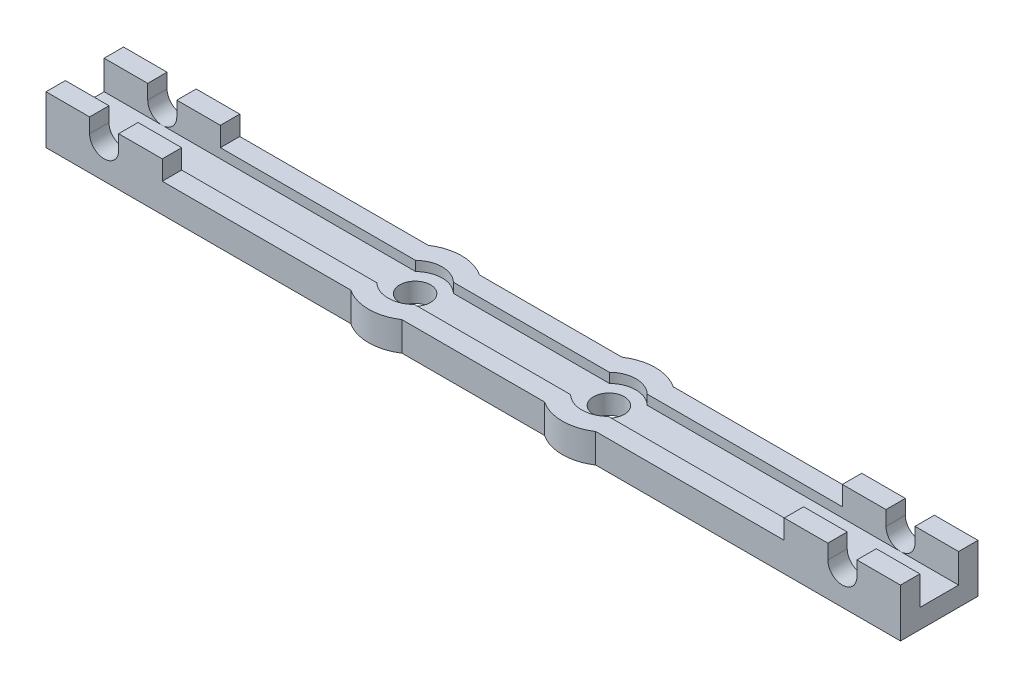
SolidWorks part; units mm, degrees
ref_plane "Front Plane" through (0, 0, 0) normal (0, 0, 1) x (1, 0, 0)
ref_plane "Top Plane" through (0, 0, 0) normal (0, 1, 0) x (1, 0, 0)
ref_plane "Right Plane" through (0, 0, 0) normal (1, 0, 0) x (0, 0, -1)
sketch "Sketch1" plane through (0, 0, 0) normal (0, 1, 0) x (1, 0, 0)
  line L1 (0, -4) -> (44.1, -4)
  line L2 (0, -4) -> (0, 4)
  line L3 (0, 4) -> (44.1, 4)
  line L4 (44.1, -4) -> (44.1, 4)
  point P4 (0, 0)
  dimension "D1" = 44.1
  dimension "D2" = 8
extrude "Boss-Extrude1" add sketch "Sketch1" along normal blind 2
sketch "Sketch2" plane through (0, 2, 0) normal (0, 1, 0) x (1, 0, 0)
  line L1 (44.1, 4) -> (32.1, 4)
  line L2 (44.1, 4) -> (44.1, 2)
  line L3 (44.1, 2) -> (32.1, 2)
  line L4 (32.1, 4) -> (32.1, 2)
  line L5 (44.1, -4) -> (32.1, -4)
  line L6 (44.1, -4) -> (44.1, -2)
  line L7 (44.1, -2) -> (32.1, -2)
  line L8 (32.1, -4) -> (32.1, -2)
  dimension "D1" = 2
  dimension "D2" = 12
extrude "Boss-Extrude2" add sketch "Sketch2" along normal blind 3
sketch "Sketch3" plane through (0, 0, 4) normal (0, 0, 1) x (1, 0, 0)
  line L0 (44.1, 5) -> (44.1, 0) construction
  line L1 (32.1, 5) -> (44.1, 5) construction
  line L2 (36.6, 3.5) -> (36.6, 5)
  line L3 (36.6, 5) -> (39.6, 5)
  line L4 (39.6, 5) -> (39.6, 3.5)
  arc A0 (36.6, 3.5) -> (39.6, 3.5) centre (38.1, 3.5) ccw
  dimension "D1" = 3
  dimension "D2" = 6
  dimension "D3" = 1.5
extrude "Cut-Extrude1" cut sketch "Sketch3" against normal through all
sketch "Sketch4" plane through (0, 2, 0) normal (0, 1, 0) x (1, 0, 0)
  line L0 (0, 4) -> (0, -4) construction
  line L1 (32.1, -4) -> (0, -4)
  line L2 (32.1, -4) -> (32.1, -2)
  line L3 (32.1, -2) -> (0, -2)
  line L4 (0, -4) -> (0, -2)
  line L6 (32.1, 2) -> (0, 2)
  line L7 (32.1, 2) -> (32.1, 4)
  line L8 (32.1, 4) -> (0, 4)
  line L9 (0, 2) -> (0, 4)
extrude "Boss-Extrude3" add sketch "Sketch4" along normal blind 1
mirror "Mirror1" about plane through (0, 0, 0) normal (1, 0, 0) of "Boss-Extrude3", "Cut-Extrude1", "Boss-Extrude2", "Boss-Extrude1"
sketch "Sketch7" plane through (0, 2, 0) normal (0, 1, 0) x (1, 0, 0)
  circle A0 centre (10, 0) radius 2.794
  point P3 (0, 0)
  point P4 (15.0484, 0)
  dimension "D1" = 5.588
  dimension "D2" = 10
extrude "Cut-Extrude3" cut sketch "Sketch7" along normal through all
sketch "Sketch8" plane through (0, 2, 0) normal (0, 1, 0) x (1, 0, 0)
  circle A0 centre (10, 0) radius 1.5875
  point P3 (0, 0)
  point P4 (0, 0)
  point P5 (0, 0)
  point P6 (9.5204, 0)
  dimension "D1" = 3.175
extrude "Cut-Extrude4" cut sketch "Sketch8" against normal through all
sketch "Sketch9" plane through (0, 3, 0) normal (0, 1, 0) x (1, 0, 0)
  line L4 (32.1, 4) -> (-32.1, 4) construction
  line L5 (12.6424, 4) -> (7.3576, 4)
  line L6 (-32.1, -4) -> (32.1, -4) construction
  line L7 (7.3576, -4) -> (12.6424, -4)
  arc A11 (7.3576, -4) -> (12.6424, -4) centre (10, 0) ccw
  arc A12 (11.951, 2) -> (8.049, 2) centre (10, 0) ccw construction
  arc A13 (12.6424, 4) -> (7.3576, 4) centre (10, 0) ccw
  dimension "D1" = 2
extrude "Boss-Extrude4" add sketch "Sketch9" against normal up to surface (3 mm away) up to face at (10, 0, 1.5875)
mirror "Mirror2" about plane through (0, 0, 0) normal (1, 0, 0) of "Boss-Extrude4", "Cut-Extrude4", "Cut-Extrude3"
